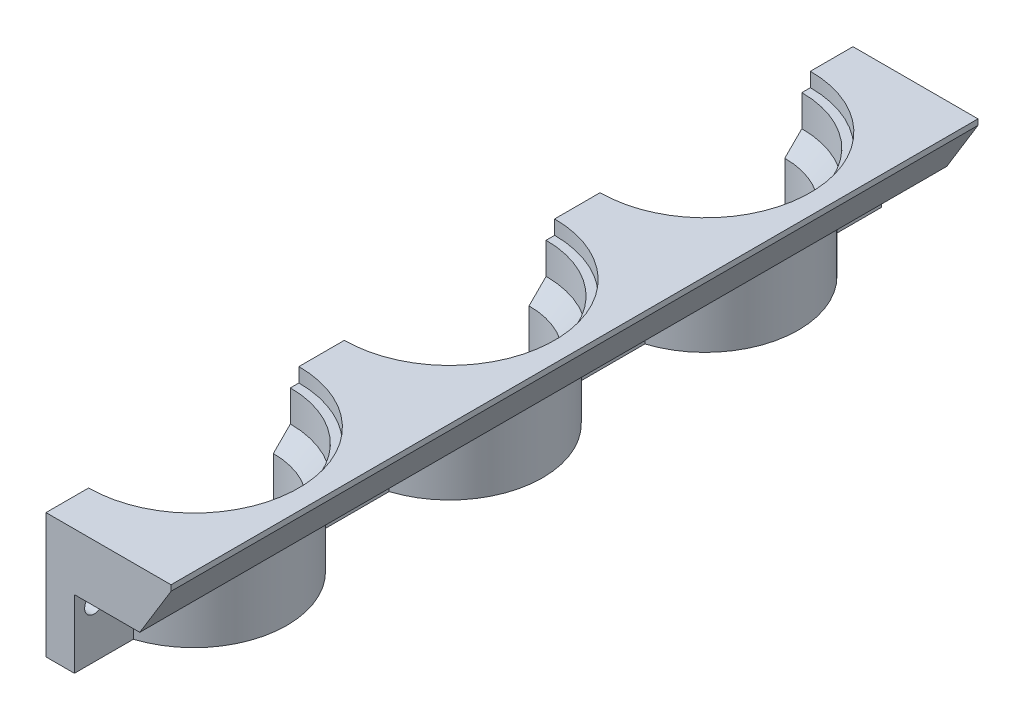
SolidWorks part; units mm, degrees
ref_plane "Płaszczyzna przednia" through (0, 0, 0) normal (0, 0, 1) x (1, 0, 0)
ref_plane "Płaszczyzna górna" through (0, 0, 0) normal (0, 1, 0) x (1, 0, 0)
ref_plane "Płaszczyzna prawa" through (0, 0, 0) normal (1, 0, 0) x (0, 0, -1)
sketch "Sketch1" plane through (0, 0, 0) normal (0, 1, 0) x (1, 0, 0)
  line L0 (0, 65.8555) -> (0, -65.8555) construction
  line L1 (0, -11.4) -> (0, -26)
  line L2 (0, -26) -> (22, -26)
  line L3 (104.3478, 45) -> (-104.3478, 45) construction
  line L4 (22, -26) -> (22, 116)
  line L5 (0, 101.4) -> (0, 116)
  line L6 (0, 116) -> (22, 116)
  line L7 (0, 11.4) -> (0, 33.6)
  line L8 (0, 56.4) -> (0, 78.6)
  arc A6 (0, -11.4) -> (0, 11.4) centre (0, 0) ccw
  arc A7 (0, 33.6) -> (0, 56.4) centre (0, 45) ccw
  arc A8 (0, 78.6) -> (0, 101.4) centre (0, 90) ccw
  point P7 (0, 0)
  point P20 (0, 45)
  point P23 (22, 45)
  dimension "D1" = 71
  dimension "D2" = 11.4
  dimension "D3" = 45
  dimension "D6" = 3
  dimension "D5" = 22
extrude "Boss-Extrude1" add sketch "Sketch1" against normal blind 10
sketch "Sketch3" plane through (0, -10, 0) normal (0, -1, 0) x (1, 0, 0)
  line L23 (0, -116) -> (0, -101.4)
  line L24 (0, -78.6) -> (0, -56.4)
  line L25 (0, -33.6) -> (0, -11.4)
  line L26 (0, 11.4) -> (0, 26)
  line L27 (5, -116) -> (5, -105.6192)
  line L28 (5, -74.3808) -> (5, -60.6192)
  line L29 (5, -29.3808) -> (5, -15.6192)
  line L30 (5, 15.6192) -> (5, 26)
  line L31 (5, -116) -> (5, -105.6192)
  line L32 (5, -74.3808) -> (5, -60.6192)
  line L33 (5, -29.3808) -> (5, -15.6192)
  line L34 (5, 15.6192) -> (5, 26)
  line L35 (0, 26) -> (5, 26)
  line L36 (0, -116) -> (5, -116)
  arc A15 (0, -101.4) -> (0, -78.6) centre (0, -90) ccw
  arc A16 (0, -56.4) -> (0, -33.6) centre (0, -45) ccw
  arc A17 (0, -11.4) -> (0, 11.4) centre (0, 0) ccw
  arc A18 (5, -105.6192) -> (5, -74.3808) centre (0, -90) ccw
  arc A19 (5, -60.6192) -> (5, -29.3808) centre (0, -45) ccw
  arc A20 (5, -15.6192) -> (5, 15.6192) centre (0, 0) ccw
  arc A21 (5, -105.6192) -> (5, -74.3808) centre (0, -90) ccw
  arc A22 (5, -60.6192) -> (5, -29.3808) centre (0, -45) ccw
  arc A23 (5, -15.6192) -> (5, 15.6192) centre (0, 0) ccw
  dimension "D1" = 5
extrude "Boss-Extrude2" add sketch "Sketch3" along normal blind 12
chamfer "Chamfer2" distance 5.5 distance2 9 1 edges at (22, -10, -45)
ref_plane "Plane1" through (0, 0, -80.5) normal (0, 0, 1) x (1, 0, 0)
sketch "Sketch6" plane through (0, 0, 0) normal (-1, 0, 0) x (0, 0, 1)
  line L0 (-101.4, 0) -> (-78.6, 0) construction
  line L1 (-76, -11) -> (-76, -26)
  line L2 (-90, 3.7296) -> (-90, -25.2968) construction
  line L3 (-90, 0) -> (-73, 0)
  line L4 (-73, 0) -> (-73, -8)
  line L5 (-90, -11) -> (-76, -11)
  line L6 (-73, -8) -> (-76, -11)
  line L7 (-90, -26) -> (-76, -26)
  line L8 (-90, 0) -> (-90, -26)
  line L10 (-90, 0) -> (-71.5, 0)
  line L11 (-90, 0) -> (-90, -2.5)
  line L12 (-90, -2.5) -> (-71.5, -2.5)
  line L13 (-71.5, 0) -> (-71.5, -2.5)
  point P3 (-90, 0)
  point P16 (-90, 0)
  dimension "D1" = 17
  dimension "D2" = 8
  dimension "D3" = 14
  dimension "D4" = 3
  dimension "D5" = 15
  dimension "D6" = 18.5
  dimension "D7" = 2.5
revolve "Cut-Revolve6" cut sketch "Sketch6" angle 360 about L8
pattern_linear "LPattern3" count 3 spacing 45 along (0, 0, 1) of "Cut-Revolve6"
sketch "Sketch7" plane through (5, 0, 0) normal (1, 0, 0) x (0, 0, -1)
  line L0 (74.3808, -10) -> (60.6192, -16) construction
  line L1 (60.6192, -22) -> (60.6192, -10) construction
  circle A0 centre (67.5, -13) radius 1.7
  point P3 (67.5, -13)
  dimension "D1" = 3.4
extrude "Cut-Extrude1" cut sketch "Sketch7" against normal blind 10
pattern_linear "LPattern4" count 3 spacing 45 along (0, 0, 1) of "Cut-Extrude1"
pattern_linear "LPattern5" count 2 spacing 45 along (0, 0, -1) of "Cut-Extrude1"
sketch "Sketch8" plane through (0, 0, 26) normal (0, 0, 1) x (1, 0, 0)
  line L1 (0, 0) -> (22, 0) construction
  line L2 (16.5, 0) -> (26.5, 0)
  line L3 (16.5, 0) -> (16.5, -15)
  line L4 (16.5, -15) -> (26.5, -15)
  line L5 (26.5, 0) -> (26.5, -15)
  circle A0 centre (22.5, -11) radius 1.6
  point P10 (0, 0)
  point P11 (0, 0)
  point P14 (23.3889, -7.5717)
  dimension "D1" = 3.2
  dimension "D2" = 10
  dimension "D3" = 15
  dimension "D4" = 6
  dimension "D5" = 11
